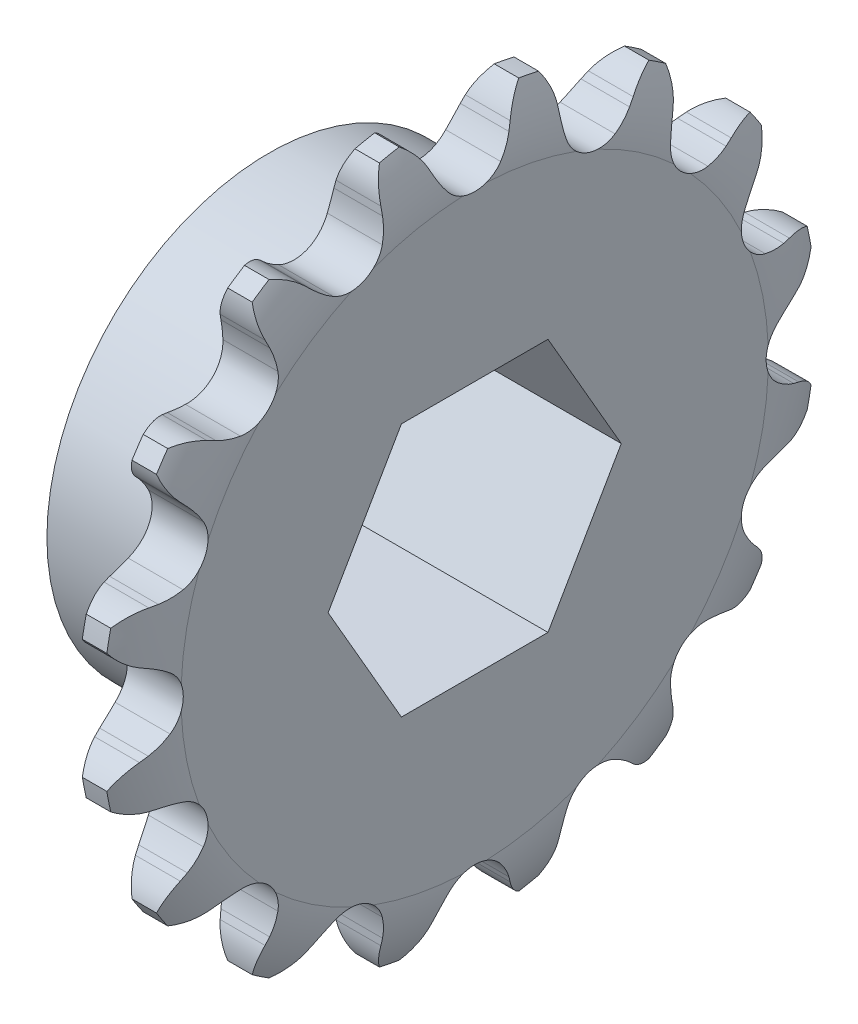
SolidWorks part; units mm, degrees
material "6061 Alloy"
ref_plane "Plane1" through (0, 0, 0) normal (0, 0, 1) x (1, 0, 0)
ref_plane "Plane2" through (0, 0, 0) normal (0, 1, 0) x (1, 0, 0)
ref_plane "Plane3" through (0, 0, 0) normal (1, 0, 0) x (0, 0, -1)
sketch "Clipboard" plane through (0, 0, 0) normal (0, 1, 0) x (1, 0, 0)
  line L0 (0, 0) -> (6.104, -1.7503)
  line L1 (-15, 0) -> (100, 0) construction
  line L2 (0, 0) -> (-0.5218, 0.5897)
  line L3 (0, 0) -> (-2.9658, 1.1335)
  line L4 (0, 0) -> (3.052, 0.8751)
  line L5 (0, 0) -> (-9.6384, -3.5949)
  line L6 (0, 0) -> (-2.3214, -1.5662)
  line L7 (-0.5218, 0.5897) -> (9.3158, 3.5974)
  line L8 (-76.2, 38.1) -> (-61.976, 38.1)
  line L9 (-73.2057, 38.5609) -> (-73.0533, 38.5634)
  line L10 (-73.0533, 76.1892) -> (-66.6525, 76.1892)
  circle A0 centre (0, 0) radius 1.651
  circle A1 centre (0, 0) radius 11.1125
  circle A2 centre (0, 0) radius 11.1125
  dimension "Dr" = 3.302
  dimension "MHD" = 22.225
  dimension "Hub_dia" = 22.225
  dimension "Num_teeth" = 16
  dimension "Pitch" = 6.35
  dimension "Width" = 3.175
  dimension "Chamfer_wid" = 0.7874
  dimension "Chamfer_dep" = 3.175
  dimension "Overall_len" = 10.287
  dimension "Show_teeth" = 16
  dimension "Thickness" = 2.8004
  dimension "OAL" = 10.2871
  dimension "T_dim" = 14.224
  dimension "Width_const" = 0.1524
  dimension "Width_factor" = 0.93
  dimension "Num_strands" = 1
  dimension "Transv_pitch" = 6.4008
sketch "BasProSke" plane through (0, 0, 0) normal (0, 1, 0) x (1, 0, 0)
  line L0 (-10, 0) -> (60, 0) construction
  line L1 (0, 0) -> (0, 14.6918)
  line L2 (0, 0) -> (2.8004, 0)
  line L3 (2.8004, 0) -> (2.8003, 14.6918)
  line L4 (2.013, 17.8668) -> (0.7874, 17.8668)
  arc A0 (0, 14.6918) -> (0.7874, 17.8668) centre (6.7949, 14.6918) cw
  arc A1 (2.8003, 14.6918) -> (2.013, 17.8668) centre (-3.9946, 14.6918) ccw
  dimension "D1" = 6.7949
  dimension "G1" = 0.7874
  dimension "G2" = 0.7874
  dimension "H2" = 3.175
  dimension "Diameter" = 35.7336
  dimension "H1" = 3.175
  dimension "Thickness" = 2.8004
revolve "Base-Revolve" add sketch "BasProSke" angle 360 about L0
sketch "GrvSke" plane through (0, 0, 0) normal (0, 1, 0) x (1, 0, 0)
  line L0 (2.8003, 14.6918) -> (2.8003, 12.4058)
  line L1 (2.8003, 12.4058) -> (6.4008, 12.4058)
  line L2 (6.4008, 12.4058) -> (6.4008, 14.6918)
  line L3 (2.0129, 17.8668) -> (7.1882, 17.8668)
  line L4 (4.6006, 0) -> (4.6006, 52.07) construction
  line L5 (-10, 0) -> (60, 0) construction
  line L6 (0, 0) -> (35.56, 0) construction
  arc A0 (6.4008, 14.6918) -> (7.1882, 17.8668) centre (13.1957, 14.6918) cw
  arc A1 (2.8003, 14.6918) -> (2.0129, 17.8668) centre (-3.9946, 14.6918) ccw
  dimension "Diameter" = 35.7336
  dimension "H1" = 3.175
  dimension "Grv_diam" = 24.8116
  dimension "Grv_width" = 3.6004
  dimension "Offset" = 4.6006
  dimension "G1" = 0.7874
revolve "Groove" [suppressed] cut sketch "GrvSke" angle 360 about L6
pattern_linear "Grooves" [suppressed]
sketch "TooCutSke" plane through (0, 0, 0) normal (1, 0, 0) x (0, 0, -1)
  line L0 (1.896, 16.1459) -> (2.0514, 16.491)
  line L1 (0, 0) -> (0, 107) construction
  line L2 (0, 16.2745) -> (-10, 16.2745) construction
  line L3 (-1.896, 16.1459) -> (-2.0514, 16.491)
  arc A0 (1.3237, 15.2121) -> (1.896, 16.1459) centre (-2.0601, 17.928) ccw
  arc A1 (1.3237, 15.2121) -> (-1.3237, 15.2121) centre (0, 16.2745) cw
  arc A2 (2.0514, 16.491) -> (4.534, 18.0955) centre (4.534, 15.3726) cw
  arc A3 (-1.3237, 15.2121) -> (-1.896, 16.1459) centre (2.0601, 17.928) cw
  arc A4 (-2.0514, 16.491) -> (-4.534, 18.0955) centre (-4.534, 15.3726) ccw
  arc A5 (4.534, 18.0955) -> (-4.534, 18.0955) centre (0, 0) ccw
  dimension "R" = 1.6974
  dimension "E" = 4.339
  dimension "F" = 2.7228
  dimension "Pitch_radius" = 16.2745
  dimension "W" = 4.534
  dimension "V" = 0.9019
  dimension "A" = 38.75
  dimension "B" = 14.5
extrude "ToothCut" cut sketch "TooCutSke" along normal through all
pattern_circular "TeethCuts" count 16 every 22.5 about axis through (-10, 0, 0) along (1, 0, 0) of "ToothCut"
sketch "HubNeaOneSke" plane through (0, 0, 0) normal (-1, 0, 0) x (0, 0, 1)
  circle A0 centre (0, 0) radius 11.1125
  dimension "Diameter" = 22.225
extrude "HubNearOne" add sketch "HubNeaOneSke" along normal blind 7.4867
sketch "HubNeaBotSke" plane through (0, 0, 0) normal (-1, 0, 0) x (0, 0, 1)
  circle A0 centre (0, 0) radius 11.1125
  dimension "Diameter" = 22.225
extrude "HubNearBoth" [suppressed] add sketch "HubNeaBotSke" along normal blind 3.7434
ref_plane "FarPln" through (2.8004, 0, 0) normal (1, 0, 0) x (0, 0, -1)
sketch "HubFarSke" plane through (2.8004, 0, 0) normal (1, 0, 0) x (0, 0, -1)
  circle A0 centre (0, 0) radius 11.1125
  dimension "Diameter" = 22.225
extrude "HubFar" [suppressed] add sketch "HubFarSke" along normal blind 3.7434
sketch "BorSke" plane through (0, 0, 0) normal (1, 0, 0) x (0, 0, -1)
  circle A0 centre (0, 0) radius 6.35
  dimension "Diameter" = 12.7
extrude "Bore" cut sketch "BorSke" along normal mid plane 20.5741
sketch "KeySke" plane through (0, 0, 0) normal (1, 0, 0) x (0, 0, -1)
  line L0 (-1.5875, 0) -> (-1.5875, 7.874)
  line L1 (-1.5875, 7.874) -> (1.5875, 7.874)
  line L2 (1.5875, 7.874) -> (1.5875, 0)
  line L3 (0, 0) -> (0, 34) construction
  line L4 (-1.5875, 0) -> (1.5875, 0)
  dimension "Offset" = 7.874
  dimension "Width" = 3.175
extrude "Keyway" [suppressed] cut sketch "KeySke" along normal mid plane 20.5741
pattern_circular "Keyway2" [suppressed] count 2 every 90 about axis through (-10, 0, 0) along (1, 0, 0)
sketch "Sketch1" plane through (2.8003, 0, 0) normal (1, 0, 0) x (0, 0, -1)
  line L1 (7.3323, 0) -> (3.6662, 6.35)
  line L2 (3.6662, 6.35) -> (-3.6662, 6.35)
  line L3 (-3.6662, 6.35) -> (-7.3323, 0)
  line L4 (-7.3323, 0) -> (-3.6662, -6.35)
  line L5 (-3.6662, -6.35) -> (3.6662, -6.35)
  line L6 (3.6662, -6.35) -> (7.3323, 0)
  circle A0 centre (0, 0) radius 6.35 construction
  circle A1 centre (0, 0) radius 6.35 construction
extrude "Cut-Extrude1" cut sketch "Sketch1" against normal through all
equation "\"Num_teeth@Clipboard\" = int( \"Num_teeth@Clipboard\" )"
equation "\"Num_teeth@Clipboard\" = ((sgn( \"Num_teeth@Clipboard\" - 5.0)+1)*( \"Num_teeth@Clipboard\" - 5.0))/2 +5.0"
equation "\"Num_teeth@Clipboard\" = ((sgn( \"Num_teeth@Clipboard\" - 200.0)-1)*( \"Num_teeth@Clipboard\" - 200.0))/-2 +200.0"
equation "\"MHD@Clipboard\" = \"Pitch@Clipboard\" * (1.0 / tan(3.14159265 / \"Num_teeth@Clipboard\" ) - 1.0) - 0.03"
equation "\"Thickness@Clipboard\"  = \"Width@Clipboard\" * \"Width_factor@Clipboard\" - \"Width_const@Clipboard\" + (\"Num_strands@Clipboard\" - 1) * \"Transv_pitch@Clipboard\""
equation "\"OAL@Clipboard\" = \"Thickness@Clipboard\""
equation "\"MHD@Clipboard\" = ((sgn( \"MHD@Clipboard\" - \"Hub_dia@Clipboard\" )-1)*( \"MHD@Clipboard\" - \"Hub_dia@Clipboard\" ))/-2+ \"Hub_dia@Clipboard\""
equation "\"OAL@Clipboard\" = ((sgn( \"OAL@Clipboard\" - \"Overall_len@Clipboard\" )+1)*( \"OAL@Clipboard\" - \"Overall_len@Clipboard\" ))/2 + \"Overall_len@Clipboard\" + 0.000002"
equation "\"Num_teeth@TeethCuts\" = int( \"Show_teeth@Clipboard\" ) + 1"
equation "\"Num_teeth@TeethCuts\" = ((sgn( \"Num_teeth@TeethCuts\" - \"Num_teeth@Clipboard\" )-1)*( \"Num_teeth@TeethCuts\" - \"Num_teeth@Clipboard\" ))/-2+ \"Num_teeth@Clipboard\""
equation "\"Num_teeth@TeethCuts\" = ((sgn( \"Num_teeth@TeethCuts\" - 2.0)+1)*( \"Num_teeth@TeethCuts\" - 2.0))/2 +2.0"
equation "\"Angle@TeethCuts\" = 360.0 / \"Num_teeth@Clipboard\""
equation "\"Pitch_radius@TooCutSke\" = ( \"Pitch@Clipboard\" / 2.0) / sin(3.14159265 / \"Num_teeth@Clipboard\" )  'ma"
equation "\"R@TooCutSke\"  = \"Dr@Clipboard\" * 0.5025 + 0.0015"
equation "\"A@TooCutSke\" = 35.0 + (60.0 / \"Num_teeth@Clipboard\")"
equation "\"E@TooCutSke\"  = \"Dr@Clipboard\" * 1.3025 + 0.0015"
equation "\"B@TooCutSke\"  = 18.0 - (56.0 / \"Num_teeth@Clipboard\" )"
equation "\"W@TooCutSke\" = 1.4 * \"Dr@Clipboard\" * cos(3.14159265 / \"Num_teeth@Clipboard\" )"
equation "\"V@TooCutSke\" = 1.4 * \"Dr@Clipboard\" * sin(3.14159265 / \"Num_teeth@Clipboard\" )"
equation "\"Diameter@BasProSke\" = 2.0 * ( (0.3 * \"Pitch@Clipboard\" ) +  \"Pitch@Clipboard\" / 2.0 / tan(3.14159265 / \"Num_teeth@Clipboard\" ))"
equation "\"Thickness@BasProSke\"  = \"Thickness@Clipboard\""
equation "\"G1@BasProSke\" =  \"Chamfer_wid@Clipboard\""
equation "\"G2@BasProSke\" =  \"Chamfer_wid@Clipboard\""
equation "\"H1@BasProSke\" =  \"Chamfer_dep@Clipboard\""
equation "\"H2@BasProSke\" =  \"Chamfer_dep@Clipboard\""
equation "\"Diameter@GrvSke\" = \"Diameter@BasProSke\""
equation "\"G1@GrvSke\" = \"Chamfer_wid@Clipboard\""
equation "\"H1@GrvSke\" = \"Chamfer_dep@Clipboard\""
equation "\"Grv_diam@GrvSke\" =  \"Pitch@Clipboard\" * (1.0 / tan(3.14159265 / \"Num_teeth@Clipboard\" ) - 1.0) - 0.03"
equation "\"Grv_width@GrvSke\" =  \"Transv_pitch@Clipboard\" - ( \"Width@Clipboard\" * \"Width_factor@Clipboard\" - \"Width_const@Clipboard\" )"
equation "\"Offset@GrvSke\" = \"Grv_width@GrvSke\" / 2.0 + ( \"Width@Clipboard\" * \"Width_factor@Clipboard\" - \"Width_const@Clipboard\" )"
equation "\"Offset@Grooves\" = \"Transv_pitch@Clipboard\""
equation "\"Num_grvs@Grooves\" = \"Num_strands@Clipboard\""
equation "\"Num_grvs@Grooves\" = \"Num_grvs@Grooves\" - 1 * sgn( \"Num_grvs@Grooves\" -1)"
equation "\"Diameter@HubNeaOneSke\" = \"MHD@Clipboard\""
equation "\"Length@HubNearOne\" = \"OAL@Clipboard\" - \"Thickness@BasProSke\""
equation "\"Diameter@HubNeaBotSke\" = \"MHD@Clipboard\""
equation "\"Length@HubNearBoth\" = ( \"OAL@Clipboard\" - \"Thickness@BasProSke\" ) / 2.0"
equation "\"Thickness@FarPln\" = \"Thickness@BasProSke\""
equation "\"Diameter@HubFarSke\" = \"MHD@Clipboard\""
equation "\"Length@HubFar\" = ( \"OAL@Clipboard\" - \"Thickness@BasProSke\" ) / 2.0"
equation "\"D1@Bore\" = \"OAL@Clipboard\" * 2.0"
equation "\"D1@Keyway\" = \"OAL@Clipboard\" * 2.0"
equation "\"Offset@KeySke\" = \"T_dim@Clipboard\" - \"Diameter@BorSke\" / 2.0"
